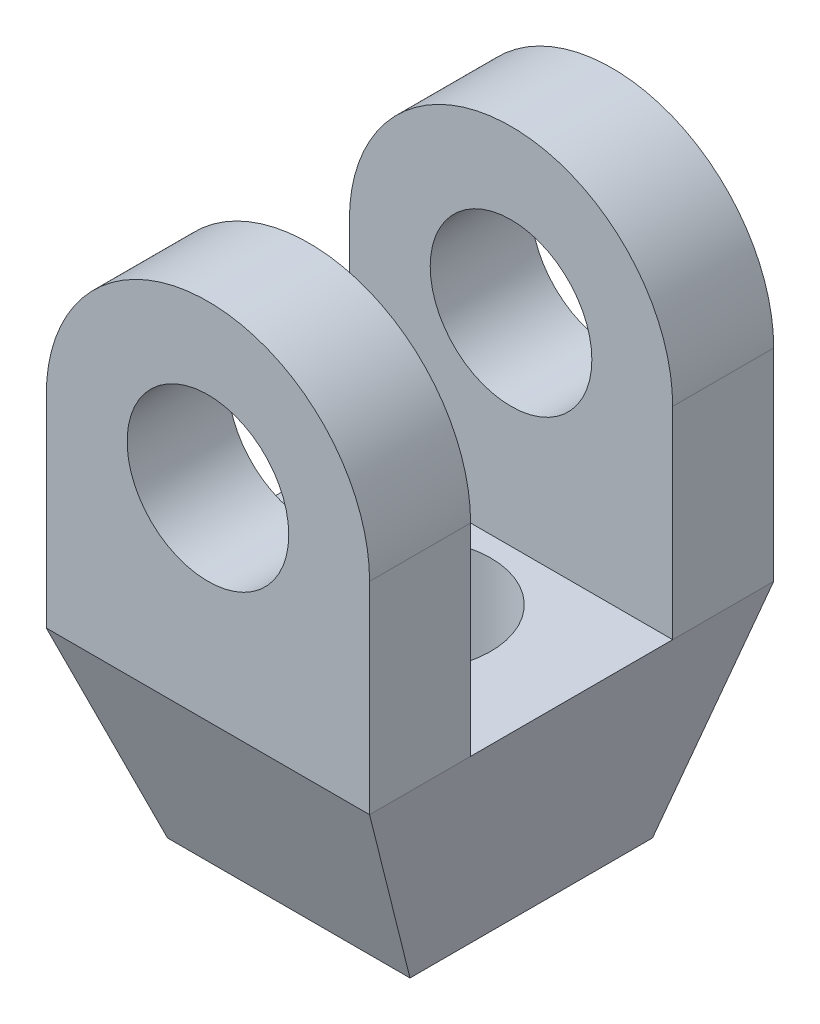
SolidWorks part; units mm, degrees
ref_plane "Front Plane" through (0, 0, 0) normal (0, 0, 1) x (1, 0, 0)
ref_plane "Top Plane" through (0, 0, 0) normal (0, 1, 0) x (1, 0, 0)
ref_plane "Right Plane" through (0, 0, 0) normal (1, 0, 0) x (0, 0, -1)
sketch "Sketch1" plane through (0, 0, 0) normal (1, 0, 0) x (0, 0, -1)
  line L0 (2.5, 7.5) -> (5, 7.5)
  line L1 (-3, -7.5) -> (3, -7.5)
  line L2 (-5, -2.5) -> (-5, 7.5)
  line L3 (-5, 7.5) -> (-2.5, 7.5)
  line L4 (5, -2.5) -> (5, 7.5)
  line L6 (-3, -7.5) -> (-5, -2.5)
  line L8 (-2.5, 7.5) -> (-2.5, -2.5)
  line L10 (2.5, 7.5) -> (2.5, -2.5)
  line L11 (0, 55) -> (0, -55) construction
  line L12 (3, -7.5) -> (5, -2.5)
  line L14 (-2.5, -2.5) -> (2.5, -2.5)
  point P0 (0, 0)
  dimension "D1" = 2.5
  dimension "D2" = 3
  dimension "D3" = 5
  dimension "D4" = 7.5
  dimension "D5" = 2.5
  dimension "D6" = 7.5
extrude "Boss-Extrude1" add sketch "Sketch1" along normal mid plane 8
sketch "Sketch2" plane through (0, 0, 5) normal (0, 0, 1) x (1, 0, 0)
  line L0 (-4, 7.5) -> (-4, -2.5) construction
  line L1 (4, -2.5) -> (-4, -2.5) construction
  circle A0 centre (0, 2.5) radius 2
  dimension "D1" = 4
  dimension "D2" = 4
  dimension "D3" = 5
extrude "Cut-Extrude1" cut sketch "Sketch2" against normal through all both and the other way through all
sketch "Sketch3" plane through (0, 0, 5) normal (0, 0, 1) x (1, 0, 0)
  line L0 (-4, 2.5) -> (-4, 7.5)
  line L1 (-4, 7.5) -> (4, 7.5)
  line L2 (4, 7.5) -> (4, 2.5)
  arc A0 (4, 2.5) -> (-4, 2.5) centre (0, 2.5) ccw
extrude "Cut-Extrude2" cut sketch "Sketch3" against normal through all both and the other way through all
sketch "Sketch5" plane through (0, 0, 0) normal (0, 0, 1) x (1, 0, 0)
  line L2 (-4, -2.5) -> (-4, -7.5)
  line L3 (4, -7.5) -> (-4, -7.5) construction
  line L4 (-3, -7.5) -> (-4, -2.5)
  line L5 (-4, -7.5) -> (-3, -7.5)
  line L6 (0, -5.5486) -> (0, 5.5486) construction
  line L7 (3, -7.5) -> (4, -2.5)
  line L8 (4, -2.5) -> (4, -7.5)
  line L9 (4, -7.5) -> (3, -7.5)
  dimension "D1" = 3
extrude "Cut-Extrude3" cut sketch "Sketch5" against normal through all both and the other way through all
sketch "Sketch8" plane through (0, -7.5, 0) normal (0, -1, 0) x (1, 0, 0)
  circle A0 centre (0, 0) radius 2
  dimension "D1" = 4
extrude "Cut-Extrude4" cut sketch "Sketch8" against normal through all both and the other way through all
